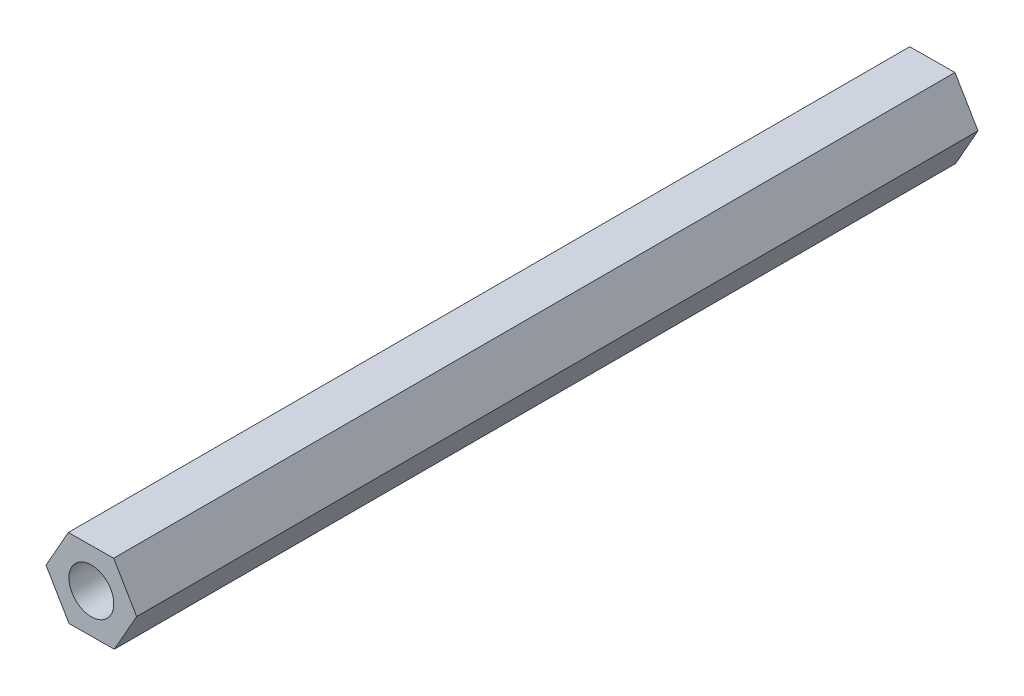
SolidWorks part; units mm, degrees
ref_plane "前视基准面" through (0, 0, 0) normal (0, 0, 1) x (1, 0, 0)
ref_plane "上视基准面" through (0, 0, 0) normal (0, 1, 0) x (1, 0, 0)
ref_plane "右视基准面" through (0, 0, 0) normal (1, 0, 0) x (0, 0, -1)
sketch "草图1" plane through (0, 0, 0) normal (0, 0, 1) x (1, 0, 0)
  line L1 (2.0515, -3.4821) -> (4.0413, 0.0356)
  line L2 (4.0413, 0.0356) -> (1.9898, 3.5177)
  line L3 (1.9898, 3.5177) -> (-2.0515, 3.4821)
  line L4 (-2.0515, 3.4821) -> (-4.0413, -0.0356)
  line L5 (-4.0413, -0.0356) -> (-1.9898, -3.5177)
  line L6 (-1.9898, -3.5177) -> (2.0515, -3.4821)
  circle A0 centre (0, 0) radius 3.5 construction
  circle A1 centre (0, 0) radius 2
extrude "凸台-拉伸1" add sketch "草图1" along normal blind 75
